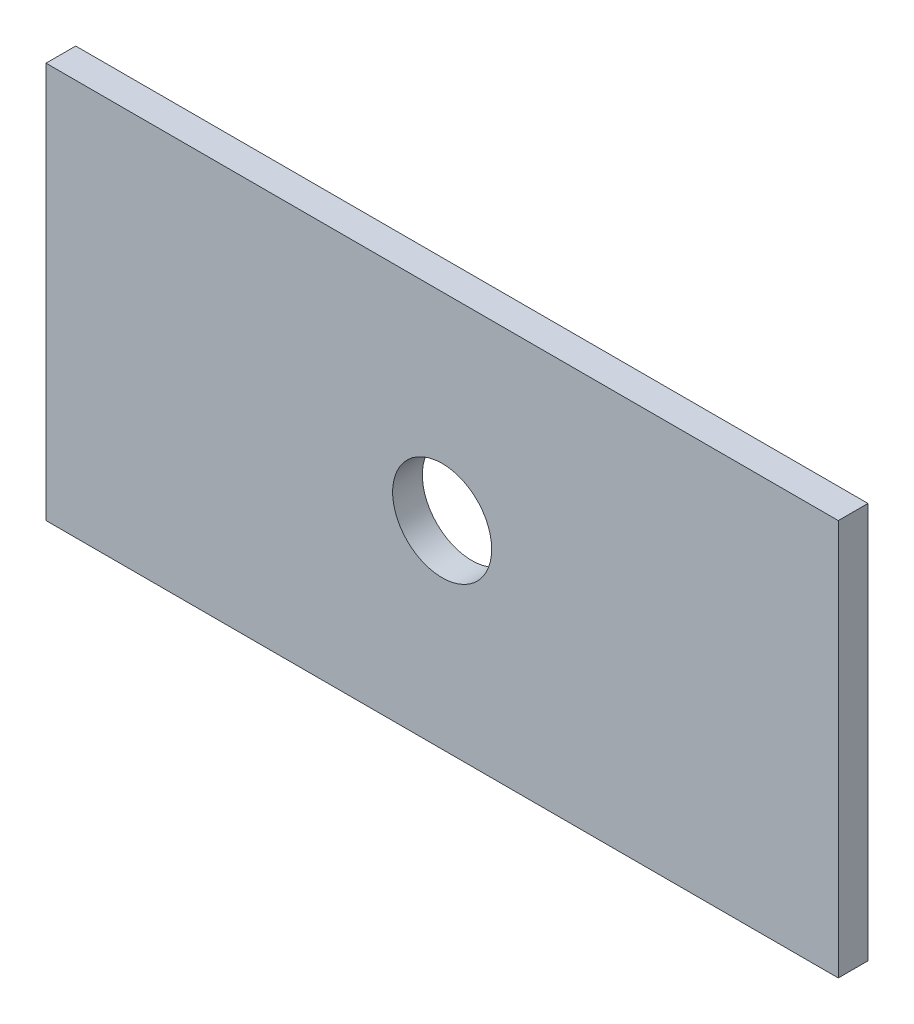
SolidWorks part; units mm, degrees
ref_plane "前视基准面" through (0, 0, 0) normal (0, 0, 1) x (1, 0, 0)
ref_plane "上视基准面" through (0, 0, 0) normal (0, 1, 0) x (1, 0, 0)
ref_plane "右视基准面" through (0, 0, 0) normal (1, 0, 0) x (0, 0, -1)
sketch "草图1" plane through (0, 0, 0) normal (0, 0, 1) x (1, 0, 0)
  line L1 (-59.7969, 26.0931) -> (20.2031, 26.0931)
  line L2 (-59.7969, 26.0931) -> (-59.7969, -13.9069)
  line L3 (-59.7969, -13.9069) -> (20.2031, -13.9069)
  line L4 (20.2031, 26.0931) -> (20.2031, -13.9069)
  line L5 (-59.7969, 26.0931) -> (20.2031, -13.9069) construction
  line L6 (-59.7969, -13.9069) -> (20.2031, 26.0931) construction
  circle A0 centre (-19.7969, 6.0931) radius 5
  point P0 (-19.7969, 6.0931)
  dimension "D1" = 10
  dimension "D2" = 80
  dimension "D3" = 40
extrude "凸台-拉伸1" add sketch "草图1" along normal blind 3
